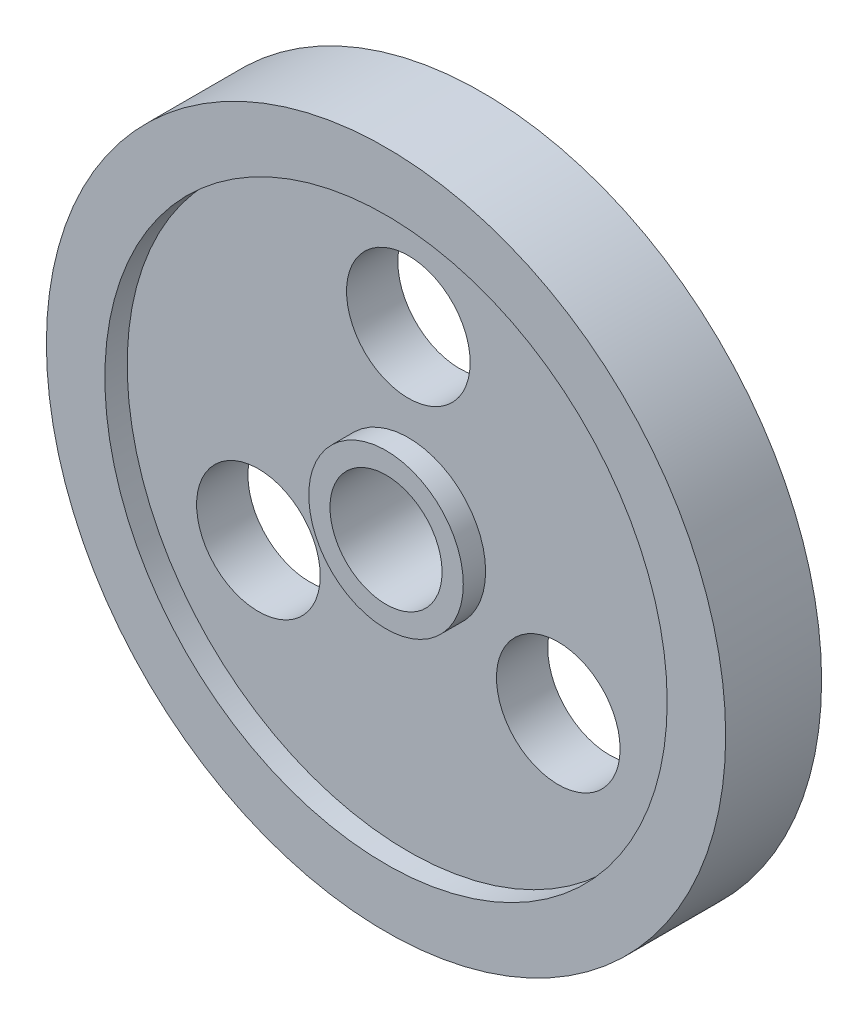
SolidWorks part; units mm, degrees
ref_plane "Front Plane" through (0, 0, 0) normal (0, 0, 1) x (1, 0, 0)
ref_plane "Top Plane" through (0, 0, 0) normal (0, 1, 0) x (1, 0, 0)
ref_plane "Right Plane" through (0, 0, 0) normal (1, 0, 0) x (0, 0, -1)
sketch "Sketch1" plane through (0, 0, 0) normal (0, 0, 1) x (1, 0, 0)
  circle A0 centre (0, 0) radius 19.781
  circle A1 centre (0, 0) radius 3.2639
  dimension "D1" = 39.5619
  dimension "D2" = 6.5278
extrude "Boss-Extrude1" add sketch "Sketch1" along normal mid plane 5.588
sketch "Sketch2" plane through (0, 0, 2.794) normal (0, 0, 1) x (1, 0, 0)
  circle A0 centre (0, 0) radius 16.375
  circle A1 centre (0, 0) radius 4.5
  dimension "D1" = 32.75
  dimension "D2" = 9
extrude "Cut-Extrude1" cut sketch "Sketch2" against normal blind 1.3
mirror "Mirror1" about plane through (0, 0, 0) normal (0, 0, 1) of "Cut-Extrude1"
sketch "Sketch3" plane through (0, 0, 1.494) normal (0, 0, 1) x (1, 0, 0)
  line L0 (0, 0) -> (0, 9.8885)
  circle A0 centre (0, 10.0825) radius 3.6
  circle A1 centre (8.7317, -5.0412) radius 3.6
  circle A2 centre (-8.7317, -5.0412) radius 3.6
  point P9 (0, 0)
  dimension "D1" = 24.6634
  dimension "D2" = 7.2
  dimension "D3" = 3
extrude "Cut-Extrude2" cut sketch "Sketch3" against normal through all
